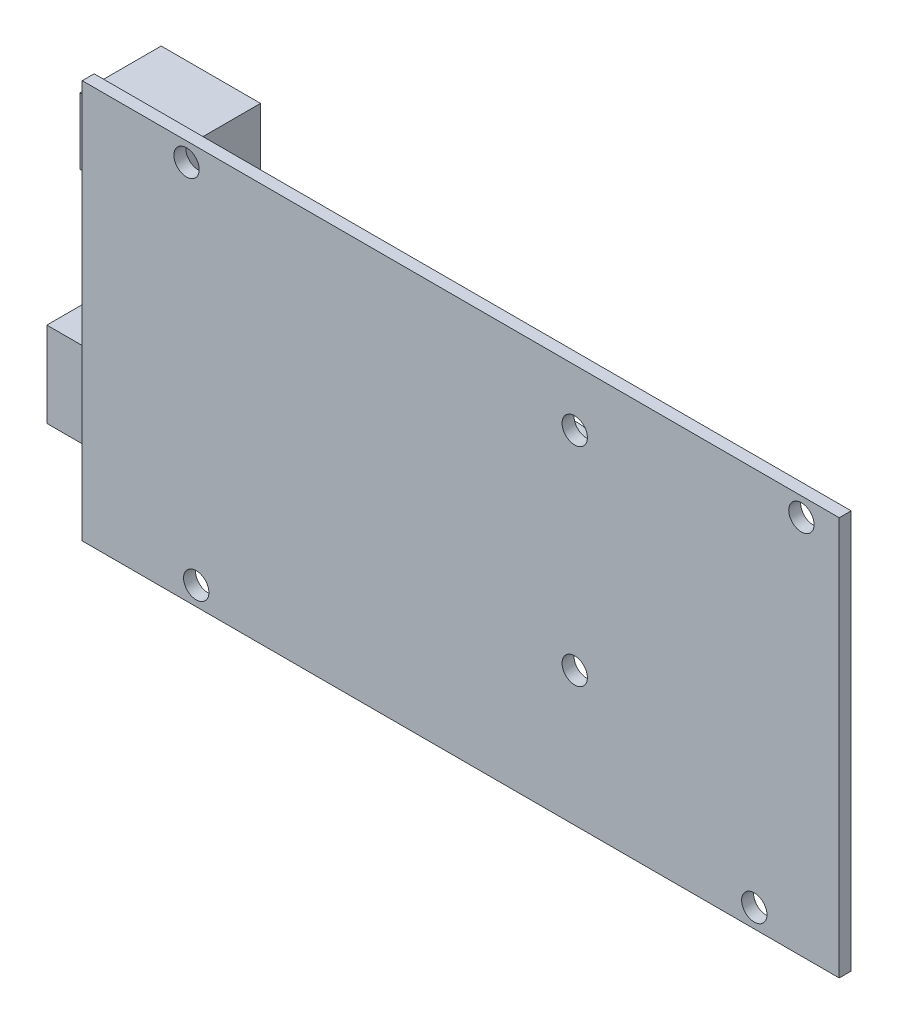
SolidWorks part; units mm, degrees
ref_plane "Front Plane" through (0, 0, 0) normal (0, 0, 1) x (1, 0, 0)
ref_plane "Top Plane" through (0, 0, 0) normal (0, 1, 0) x (1, 0, 0)
ref_plane "Right Plane" through (0, 0, 0) normal (1, 0, 0) x (0, 0, -1)
sketch "Sketch1" plane through (0, 0, 0) normal (0, 0, 1) x (1, 0, 0)
  line L1 (-50.8, -26.75) -> (50.8, -26.75)
  line L2 (-50.8, -26.75) -> (-50.8, 26.75)
  line L3 (-50.8, 26.75) -> (50.8, 26.75)
  line L4 (50.8, -26.75) -> (50.8, 26.75)
  line L5 (0, 26.75) -> (0, -26.75) construction
  line L6 (-50.8, 0) -> (50.8, 0) construction
  point P0 (0, 0)
  dimension "D1" = 53.5
  dimension "D2" = 101.6
extrude "Boss-Extrude1" add sketch "Sketch1" along normal blind 1.6
hole_wizard "M3 Clearance Hole1" positions "Sketch3" profile "Sketch4" hole size "M3" standard "ANSI Metric" end condition up to next
sketch "Sketch3" plane through (0, 0, 0) normal (0, 0, -1) x (-1, 0, 0)
  line L2 (50.8, 26.75) -> (50.8, -26.75) construction
  line L3 (50.8, -26.75) -> (-50.8, -26.75) construction
  line L4 (-50.8, 26.75) -> (50.8, 26.75) construction
  point P0 (-15.3, 19.15)
  point P2 (-45.72, 24.25)
  point P4 (-15.3, -8.75)
  point P6 (-39.4, -24.25)
  point P8 (35.5, -24.25)
  point P10 (36.8, 24.25)
  point P17 (0, 0)
  point P20 (0, 0)
  point P25 (0, 0)
  dimension "D1" = 14
  dimension "D2" = 15.3
  dimension "D3" = 2.5
  dimension "D4" = 2.5
  dimension "D5" = 2.5
  dimension "D6" = 2.5
  dimension "D7" = 7.6
  dimension "D8" = 35.5
  dimension "D9" = 66.1
  dimension "D10" = 66.1
  dimension "D11" = 90.2
  dimension "D12" = 96.52
sketch "Sketch4" plane through (15.3, 19.15, 0) normal (1, 0, 0) x (0, 1, 0)
  line L0 (0, 0) -> (0, 1.6)
  line L1 (0, 1.6) -> (1.7, 1.6)
  line L2 (1.7, 1.6) -> (1.7, 0)
  line L5 (1.7, 0) -> (0, 0)
  line L11 (0, -6.35) -> (0, 107.95) construction
  dimension "Thru Hole Dia." = 3.4
  dimension "Thru Hole Depth" = 1.6
sketch "Sketch5" plane through (0, 0, 0) normal (0, 0, -1) x (-1, 0, 0)
  line L0 (50.8, 26.75) -> (50.8, -26.75) construction
  line L1 (41.275, -17.065) -> (57.15, -17.065)
  line L2 (41.275, -17.065) -> (41.275, -5.635)
  line L3 (41.275, -5.635) -> (57.15, -5.635)
  line L4 (57.15, -17.065) -> (57.15, -5.635)
  line L5 (-50.8, 26.75) -> (50.8, 26.75) construction
  point P6 (41.275, -11.35)
  dimension "D1" = 6.35
  dimension "D2" = 9.525
  dimension "D3" = 32.385
  dimension "D4" = 43.815
extrude "Boss-Extrude2" add sketch "Sketch5" along normal blind 10.9
sketch "Sketch6" plane through (0, 0, 0) normal (0, 0, -1) x (-1, 0, 0)
  line L0 (50.8, 26.75) -> (50.8, -5.635) construction
  line L1 (39.37, 14.685) -> (52.705, 14.685)
  line L2 (39.37, 14.685) -> (39.37, 23.575)
  line L3 (39.37, 23.575) -> (52.705, 23.575)
  line L4 (52.705, 14.685) -> (52.705, 23.575)
  line L5 (-50.8, 26.75) -> (50.8, 26.75) construction
  dimension "D1" = 1.905
  dimension "D2" = 11.43
  dimension "D3" = 3.175
  dimension "D4" = 12.065
extrude "Boss-Extrude3" add sketch "Sketch6" along normal blind 10.9
sketch "Sketch7" plane through (0, 0, 0) normal (0, 0, -1) x (-1, 0, 0)
  circle A0 centre (0, 0) radius 4.6584
  point P3 (0, 0)
extrude "Boss-Extrude4" add sketch "Sketch7" along normal blind 14 contours A0
